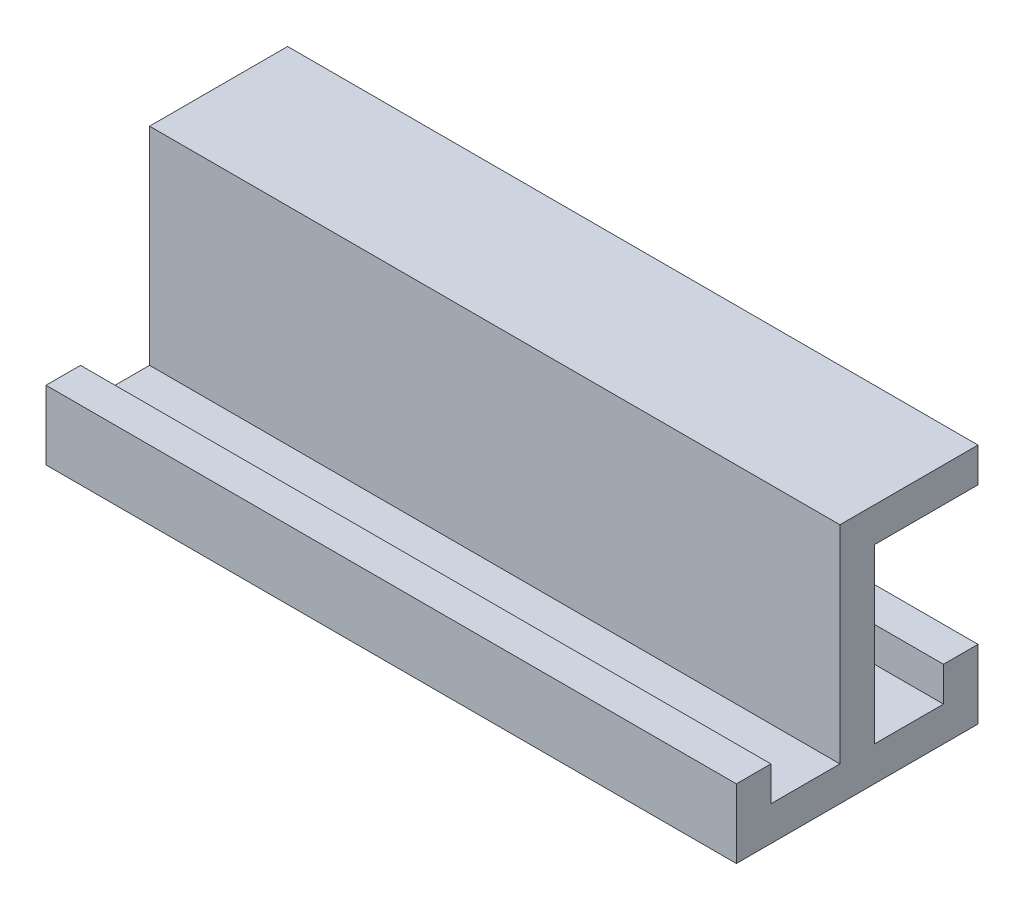
SolidWorks part; units mm, degrees
ref_plane "Спереди" through (0, 0, 0) normal (0, 0, 1) x (1, 0, 0)
ref_plane "Сверху" through (0, 0, 0) normal (0, 1, 0) x (1, 0, 0)
ref_plane "Справа" through (0, 0, 0) normal (1, 0, 0) x (0, 0, -1)
sketch "Эскиз1" plane through (0, 0, 0) normal (1, 0, 0) x (0, 0, -1)
  line L1 (-35, -5) -> (35, -5)
  line L2 (-35, -5) -> (-35, 5)
  line L3 (-35, 5) -> (35, 5)
  line L4 (35, -5) -> (35, 5)
  line L5 (-35, -5) -> (35, 5) construction
  line L6 (-35, 5) -> (35, -5) construction
  line L7 (-5, 65) -> (5, 65)
  line L8 (-5, 65) -> (-5, 5)
  line L9 (-5, 5) -> (5, 5)
  line L10 (5, 65) -> (5, 5)
  line L11 (-5, 65) -> (5, 5) construction
  line L12 (-5, 5) -> (5, 65) construction
  line L13 (5, 65) -> (35, 65)
  line L14 (5, 65) -> (5, 55)
  line L15 (5, 55) -> (35, 55)
  line L16 (35, 65) -> (35, 55)
  line L17 (35, 5) -> (25, 5)
  line L18 (35, 5) -> (35, 15)
  line L19 (35, 15) -> (25, 15)
  line L20 (25, 5) -> (25, 15)
  line L21 (-35, 5) -> (-25, 5)
  line L22 (-35, 5) -> (-35, 15)
  line L23 (-35, 15) -> (-25, 15)
  line L24 (-25, 5) -> (-25, 15)
  point P0 (0, 0)
  point P6 (0, 35)
  dimension "D1" = 70
  dimension "D2" = 10
  dimension "D3" = 60
  dimension "D4" = 10
extrude "Бобышка-Вытянуть1" add sketch "Эскиз1" along normal mid plane 200 contours L10 L7 L8 L3 | L16 L13 L10 L15 | L1 L4 L3 L2 | L20 L3 L18 L19 | L3 L24 L23 L22
